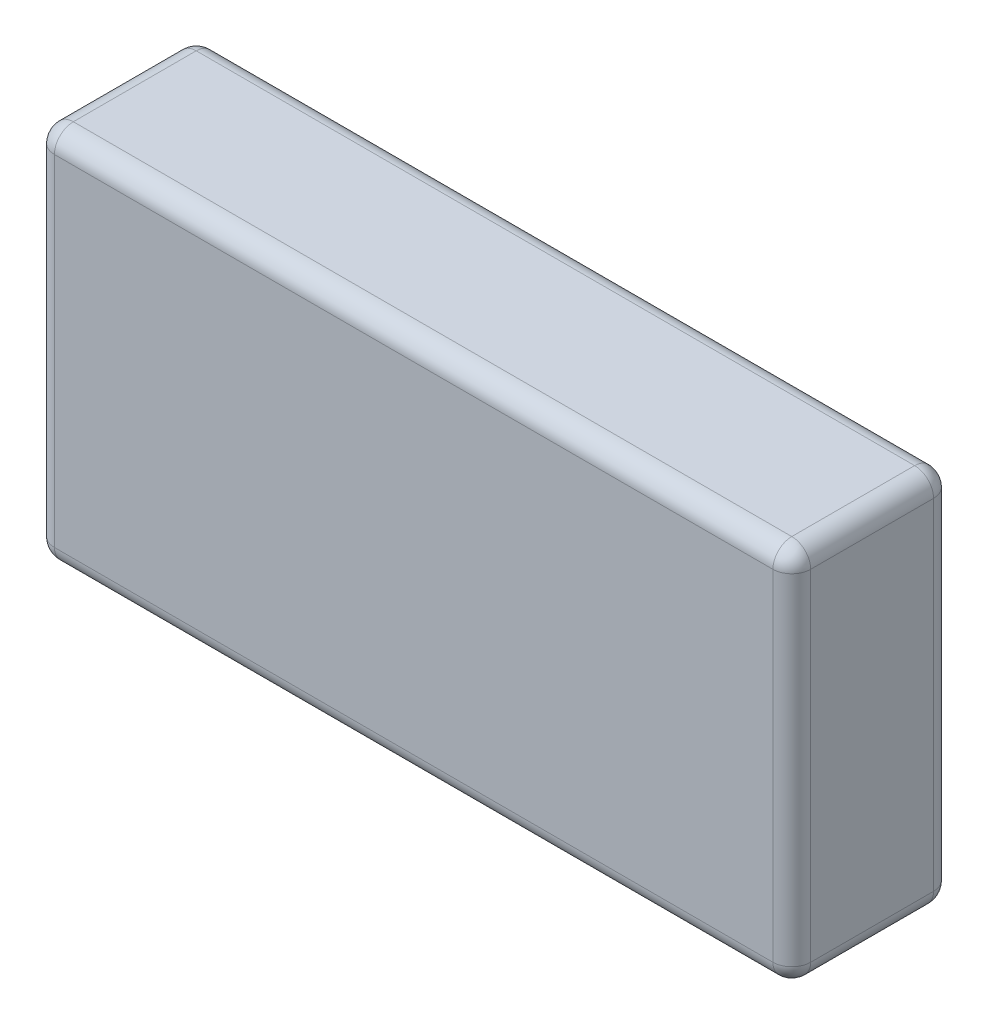
SolidWorks part; units mm, degrees
ref_plane "前视基准面" through (0, 0, 0) normal (0, 0, 1) x (1, 0, 0)
ref_plane "上视基准面" through (0, 0, 0) normal (0, 1, 0) x (1, 0, 0)
ref_plane "右视基准面" through (0, 0, 0) normal (1, 0, 0) x (0, 0, -1)
sketch "草图1" plane through (0, 0, 0) normal (0, 0, 1) x (1, 0, 0)
  line L0 (0, 0) -> (80, 0)
  line L1 (0, 0) -> (0, 40)
  line L2 (0, 40) -> (80, 40)
  line L3 (80, 40) -> (80, 0)
  dimension "D1" = 80
  dimension "D2" = 40
extrude "凸台-拉伸1" add sketch "草图1" along normal blind 17
fillet "圆角1" radius 2 4 edges at (0, 0, 8.5) (80, 0, 8.5) (80, 40, 8.5) (0, 40, 8.5)
fillet "圆角2" radius 2 16 edges at (79.4142, 39.4142, 0) (79.4142, 0.5858, 0) (0.5858, 0.5858, 0) (0.5858, 39.4142, 0) (79.4142, 39.4142, 17) (79.4142, 0.5858, 17) (0.5858, 0.5858, 17) (0.5858, 39.4142, 17) (40, 0, 0) (80, 20, 0) (0, 20, 0) (40, 40, 0) (80, 20, 17) (40, 0, 17) (0, 20, 17) (40, 40, 17)
